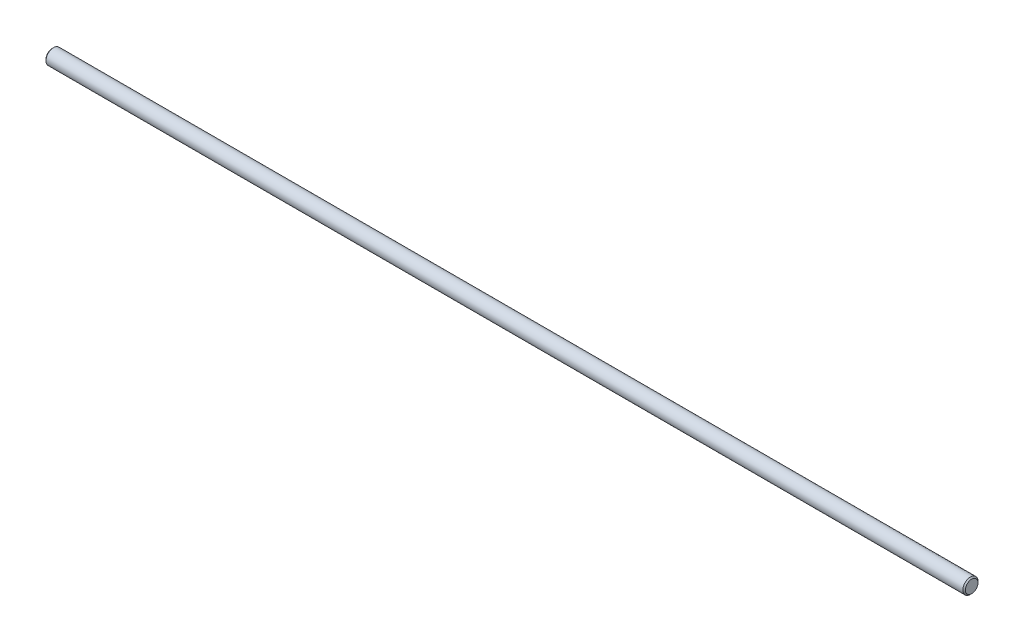
SolidWorks part; units mm, degrees
ref_plane "Płaszczyzna przednia" through (0, 0, 0) normal (0, 0, 1) x (1, 0, 0)
ref_plane "Płaszczyzna górna" through (0, 0, 0) normal (0, 1, 0) x (1, 0, 0)
ref_plane "Płaszczyzna prawa" through (0, 0, 0) normal (1, 0, 0) x (0, 0, -1)
sketch "Szkic1" plane through (0, 0, 0) normal (1, 0, 0) x (0, 0, -1)
  circle A0 centre (-47.4, 2.52) radius 3
  dimension "D1" = 6
extrude "Dodanie-wyciągnięcie1" add sketch "Szkic1" against normal blind 364
chamfer "Sfazowanie1" distance 0.5 angle 45 2 edges at (-364, 2.52, 44.4) (0, 2.52, 44.4)
